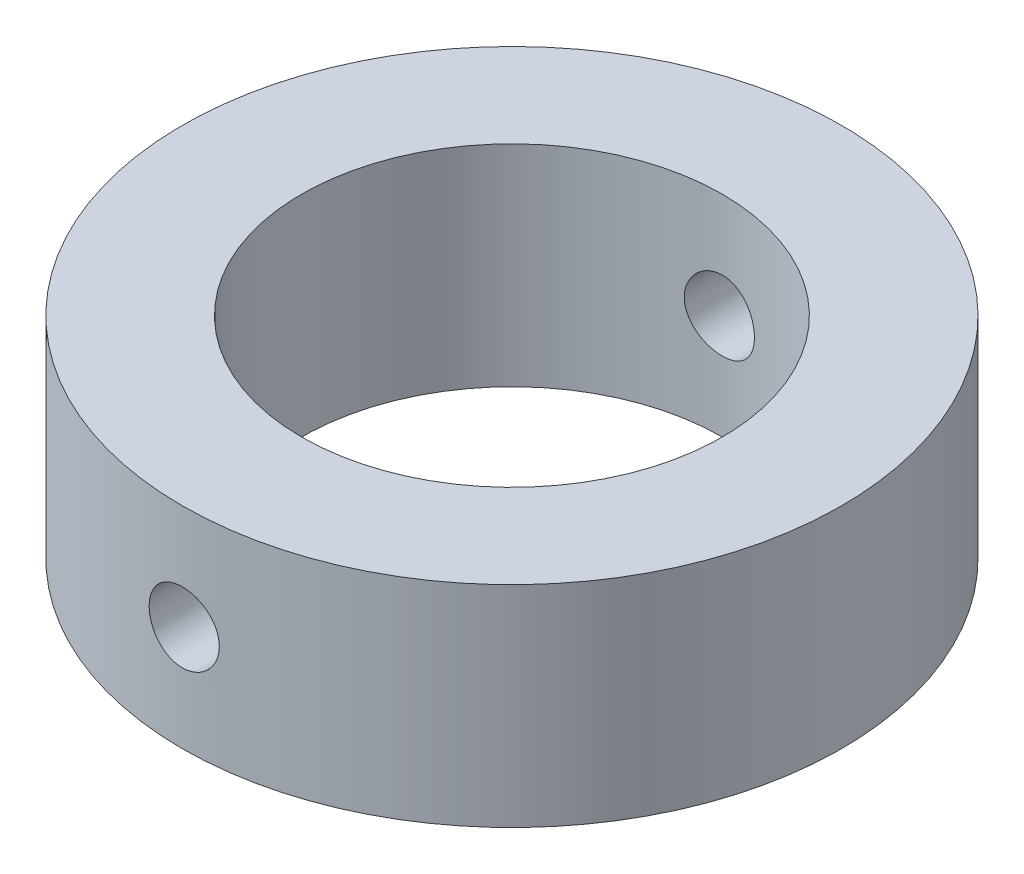
SolidWorks part; units mm, degrees
ref_plane "Спереди" through (0, 0, 0) normal (0, 0, 1) x (1, 0, 0)
ref_plane "Сверху" through (0, 0, 0) normal (0, 1, 0) x (1, 0, 0)
ref_plane "Справа" through (0, 0, 0) normal (1, 0, 0) x (0, 0, -1)
sketch "Эскиз1" plane through (0, 0, 0) normal (0, 1, 0) x (1, 0, 0)
  circle A0 centre (0, 0) radius 15
  circle A1 centre (0, 0) radius 23.5
  dimension "D1" = 30
  dimension "D2" = 47
extrude "Бобышка-Вытянуть1" add sketch "Эскиз1" along normal blind 15
sketch "Эскиз2" plane through (0, 0, 0) normal (0, 0, 1) x (1, 0, 0)
  line L0 (-23.5, 7.5) -> (23.5, 7.5) construction
  line L1 (-23.5, 15) -> (-23.5, 0) construction
  line L2 (23.5, 0) -> (23.5, 15) construction
  line L3 (23.5, 7.5) -> (0, 15) construction
  line L4 (15, 15) -> (-15, 15) construction
  line L5 (0, 15) -> (0, 0) construction
  circle A0 centre (0, 7.5) radius 2.5
  dimension "D1" = 5
extrude "Вырез-Вытянуть1" cut sketch "Эскиз2" against normal blind 44 and the other way blind 46
